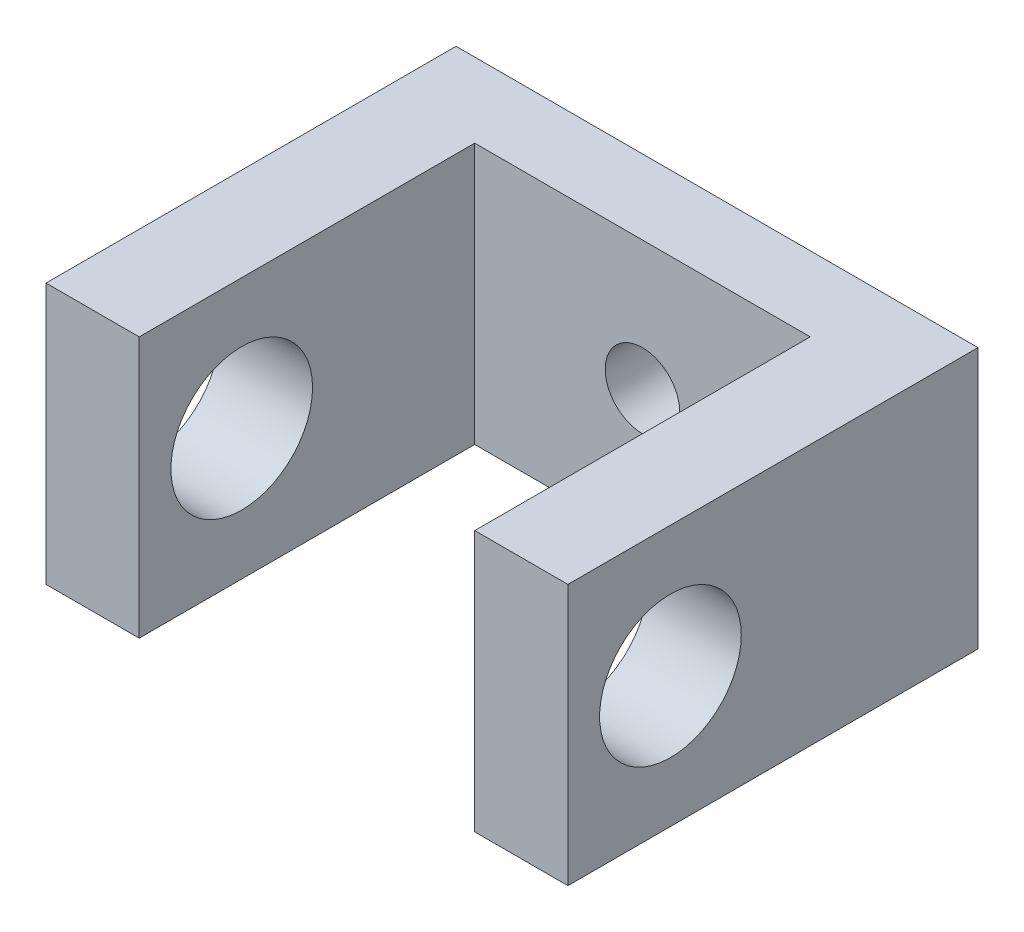
SolidWorks part; units mm, degrees
ref_plane "Спереди" through (0, 0, 0) normal (0, 0, 1) x (1, 0, 0)
ref_plane "Сверху" through (0, 0, 0) normal (0, 1, 0) x (1, 0, 0)
ref_plane "Справа" through (0, 0, 0) normal (1, 0, 0) x (0, 0, -1)
sketch "Эскиз1" plane through (0, 0, 0) normal (0, 0, 1) x (1, 0, 0)
  line L1 (-14, -7) -> (14, -7)
  line L2 (-14, -7) -> (-14, 7)
  line L3 (-14, 7) -> (14, 7)
  line L4 (14, -7) -> (14, 7)
  line L5 (-14, -7) -> (14, 7) construction
  line L6 (-14, 7) -> (14, -7) construction
  point P0 (0, 0)
  dimension "D1" = 28
  dimension "D2" = 14
extrude "Бобышка-Вытянуть1" add sketch "Эскиз1" along normal blind 22
sketch "Эскиз2" plane through (0, -7, 0) normal (0, -1, 0) x (1, 0, 0)
  line L1 (-9, 22) -> (9, 22)
  line L2 (-14, 22) -> (14, 22) construction
  line L3 (9, 22) -> (9, 4)
  line L4 (9, 4) -> (-9, 4)
  line L5 (-9, 4) -> (-9, 22)
  line L6 (-14, 0) -> (14, 0) construction
  dimension "D1" = 5
  dimension "D2" = 5
  dimension "D3" = 4
extrude "Вырез-Вытянуть1" cut sketch "Эскиз2" against normal blind 22
sketch "Эскиз3" plane through (14, 0, 0) normal (1, 0, 0) x (0, 0, -1)
  line L0 (-22, 7) -> (0, 7) construction
  line L1 (-22, -7) -> (-11, -7) construction
  line L2 (-22, -7) -> (-22, 7) construction
  line L3 (-22, 7) -> (-11, 7) construction
  line L4 (-11, -7) -> (-11, 7) construction
  line L5 (-11, -7) -> (-22, 7) construction
  line L6 (-22, -7) -> (-11, 7) construction
  circle A0 centre (-16.5, 0) radius 3.8
extrude "Вырез-Вытянуть2" cut sketch "Эскиз3" against normal blind 29
sketch "Эскиз4" plane through (0, 0, 4) normal (0, 0, 1) x (1, 0, 0)
  line L0 (9, -7) -> (-9, 7) construction
  line L1 (-9, -7) -> (9, 7) construction
  line L2 (-9, 7) -> (9, 7) construction
  circle A0 centre (0, 0) radius 2
extrude "Вырез-Вытянуть3" cut sketch "Эскиз4" against normal blind 29
